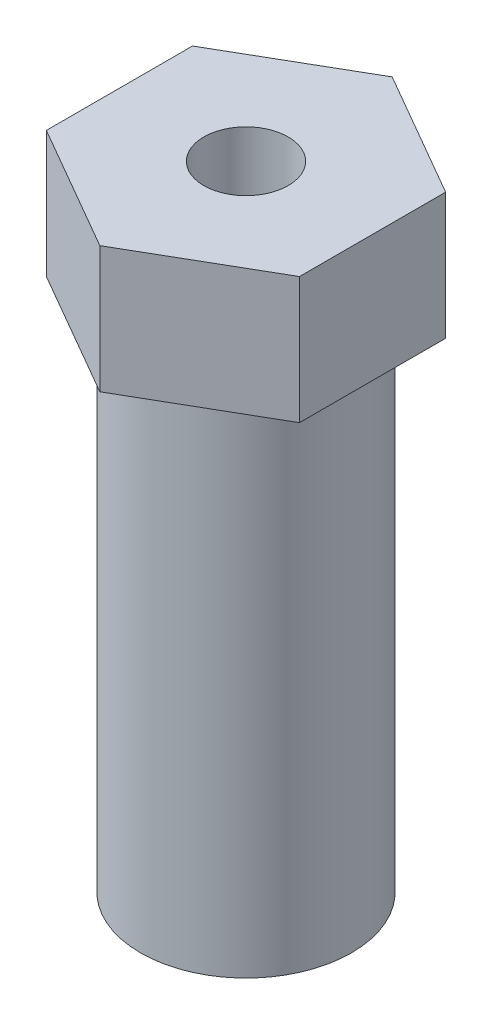
SolidWorks part; units mm, degrees
ref_plane "前视基准面" through (0, 0, 0) normal (0, 0, 1) x (1, 0, 0)
ref_plane "上视基准面" through (0, 0, 0) normal (0, 1, 0) x (1, 0, 0)
ref_plane "右视基准面" through (0, 0, 0) normal (1, 0, 0) x (0, 0, -1)
other "Configuration Table"
sketch "草图1" plane through (0, 0, 0) normal (0, 1, 0) x (1, 0, 0)
  circle A0 centre (0, 0) radius 5
  circle A1 centre (0, 0) radius 2.5
  dimension "D1" = 10
  dimension "D2" = 5
extrude "凸台-拉伸1" add sketch "草图1" along normal blind 30
sketch "草图2" plane through (0, 30, 0) normal (0, 1, 0) x (1, 0, 0)
  line L1 (0, 6.9282) -> (-6, 3.4641)
  line L2 (-6, 3.4641) -> (-6, -3.4641)
  line L3 (-6, -3.4641) -> (0, -6.9282)
  line L4 (0, -6.9282) -> (6, -3.4641)
  line L5 (6, -3.4641) -> (6, 3.4641)
  line L6 (6, 3.4641) -> (0, 6.9282)
  circle A0 centre (0, 0) radius 2
  circle A1 centre (0, 0) radius 6 construction
  dimension "D1" = 4
  dimension "D2" = 12
extrude "凸台-拉伸2" add sketch "草图2" against normal blind 6
